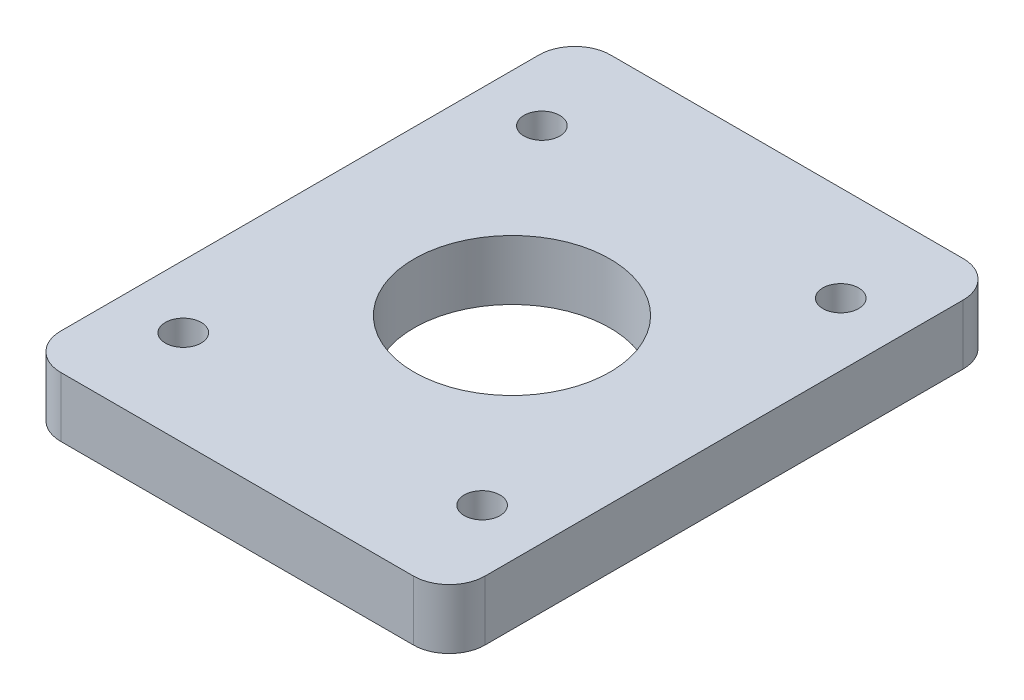
SolidWorks part; units mm, degrees
ref_plane "前视基准面" through (0, 0, 0) normal (0, 0, 1) x (1, 0, 0)
ref_plane "上视基准面" through (0, 0, 0) normal (0, 1, 0) x (1, 0, 0)
ref_plane "右视基准面" through (0, 0, 0) normal (1, 0, 0) x (0, 0, -1)
sketch "草图1" plane through (0, 0, 0) normal (0, 1, 0) x (1, 0, 0)
  line L6 (-17.75, -15.75) -> (17.75, -15.75)
  line L7 (-17.75, -15.75) -> (-17.75, 30.25)
  line L8 (17.75, -15.75) -> (17.75, 30.25)
  line L9 (-17.75, 30.25) -> (17.75, 30.25)
  line L10 (-17.75, -15.75) -> (17.75, 30.25) construction
  line L11 (17.75, -15.75) -> (-17.75, 30.25) construction
  circle A0 centre (0, 7.25) radius 8.2
  point P1 (0, 0)
  point P2 (0, 7.25)
  dimension "D1" = 16.4
  dimension "D2" = 46
  dimension "D3" = 35.5
extrude "凸台-拉伸1" add sketch "草图1" along normal blind 5
fillet "圆角2" radius 3 4 edges at (17.75, 2.5, 15.75) (-17.75, 2.5, 15.75) (-17.75, 2.5, -30.25) (17.75, 2.5, -30.25)
sketch "草图2" plane through (0, 5, 0) normal (0, 1, 0) x (1, 0, 0)
  line L0 (10, -23.1319) -> (10, 23.1319)
  line L1 (10, -23.1319) -> (-10, -23.1319)
  line L2 (10, 23.1319) -> (-10, 23.1319)
  line L3 (-10, -23.1319) -> (-10, 23.1319)
  line L4 (10, -23.1319) -> (-10, 23.1319) construction
  line L5 (10, 23.1319) -> (-10, -23.1319) construction
  line L6 (12.5, -6.75) -> (12.5, 6.75)
  line L7 (-14.75, -15.75) -> (14.75, -15.75) construction
  line L8 (12.5, -6.75) -> (-12.5, -6.75)
  line L9 (12.5, 6.75) -> (-12.5, 6.75)
  line L10 (-12.5, -6.75) -> (-12.5, 6.75)
  line L11 (12.5, -6.75) -> (-12.5, 6.75) construction
  line L12 (12.5, 6.75) -> (-12.5, -6.75) construction
  circle A2 centre (-12.5, -6.75) radius 1.5
  circle A3 centre (-12.5, 6.75) radius 1.5
  circle A4 centre (12.5, 6.75) radius 1.5
  circle A5 centre (12.5, -6.75) radius 1.5
  point P1 (0, 0)
  point P2 (0, 0)
  dimension "D2" = 2.5
  dimension "D3" = 9
  dimension "D1" = 20
sketch "草图3" plane through (0, 0, 0) normal (0, -1, 0) x (1, 0, 0)
  line L0 (-17.75, -7.25) -> (26.7138, -7.25) construction
  line L1 (-17.75, -27.25) -> (-17.75, 12.75) construction
  line L2 (0, 15.75) -> (0, -23.323) construction
  line L3 (-14.75, 15.75) -> (14.75, 15.75) construction
  circle A0 centre (-12.5, 7.75) radius 1.5
  circle A2 centre (12.5, 7.75) radius 1.5
  circle A3 centre (12.5, -22.25) radius 1.5
  circle A4 centre (-12.5, -22.25) radius 1.5
  dimension "D1" = 25
  dimension "D2" = 30
extrude "切除-拉伸1" cut sketch "草图3" against normal blind 10
